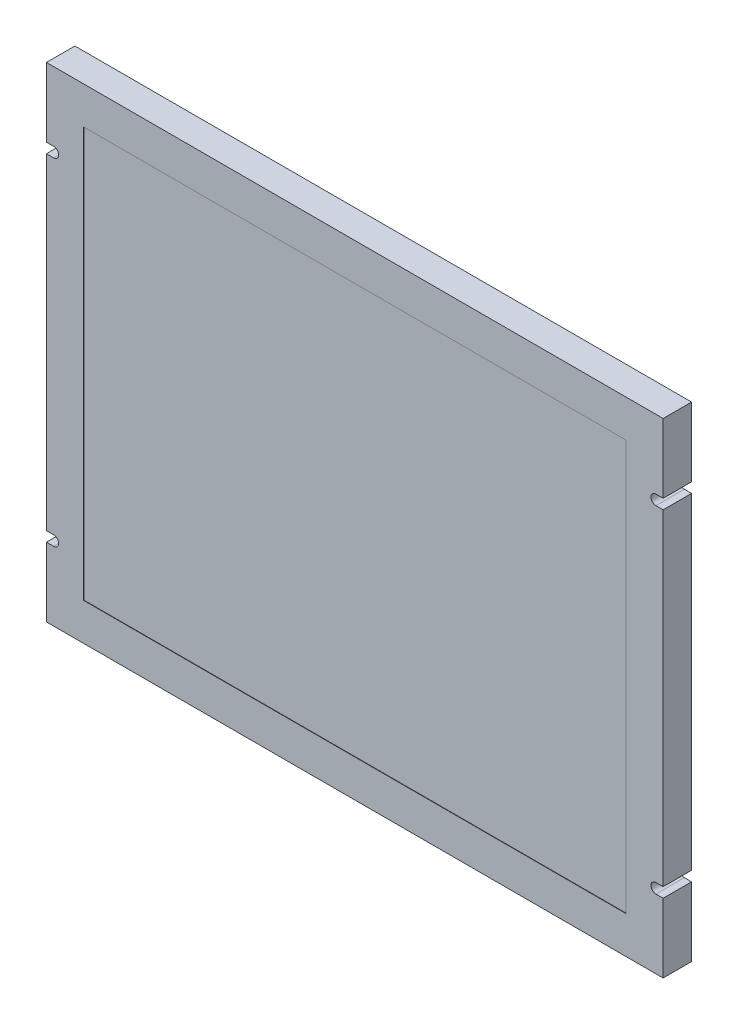
SolidWorks part; units mm, degrees
ref_plane "Front" through (0, 0, 0) normal (0, 0, 1) x (1, 0, 0)
ref_plane "Top" through (0, 0, 0) normal (0, 1, 0) x (1, 0, 0)
ref_plane "Right" through (0, 0, 0) normal (1, 0, 0) x (0, 0, -1)
sketch "Sketch1" plane through (0, 0, 0) normal (0, 0, 1) x (1, 0, 0)
  line L1 (0, 0) -> (154, 0)
  line L2 (0, 0) -> (0, -121)
  line L3 (0, -121) -> (154, -121)
  line L4 (154, 0) -> (154, -121)
  dimension "D1" = 154
  dimension "D2" = 121
extrude "Extrude1" add sketch "Sketch1" along normal blind 7.1
sketch "Sketch2" plane through (0, 0, 7.1) normal (0, 0, 1) x (1, 0, 0)
  line L0 (154, -121) -> (154, 0) construction
  line L1 (9.25, -9.3) -> (144.75, -9.3)
  line L2 (9.25, -9.3) -> (9.25, -111.7)
  line L3 (9.25, -111.7) -> (144.75, -111.7)
  line L4 (144.75, -9.3) -> (144.75, -111.7)
  line L5 (154, 0) -> (0, 0) construction
  dimension "D1" = 135.5
  dimension "D2" = 102.4
  dimension "D3" = 9.25
  dimension "D4" = 9.3
extrude "Bezel Opening" cut sketch "Sketch2" against normal blind 0.1
sketch "Sketch3" plane through (0, 0, 7.1) normal (0, 0, 1) x (1, 0, 0)
  line L2 (154, -17.25) -> (152.2, -17.25)
  line L3 (154, -121) -> (154, 0) construction
  line L4 (154, -19.75) -> (152.2, -19.75)
  line L5 (154, 0) -> (0, 0) construction
  arc A0 (152.2, -19.75) -> (152.2, -17.25) centre (152.2, -18.5) cw
  arc A1 (154, -17.25) -> (154, -19.75) centre (154, -18.5) cw
  dimension "D1" = 2.5
  dimension "D3" = 18.5
  dimension "D2" = 1.8
extrude "Cut-Extrude3" cut sketch "Sketch3" against normal blind 10
pattern_linear "LPattern1" count 2 spacing 84 along (0, -1, 0) count 2 spacing 152.2 along (-1, 0, 0) of "Cut-Extrude3"
sketch "Sketch4" plane through (0, 0, 7.1) normal (0, 0, 1) x (1, 0, 0)
  line L0 (77, 0) -> (77, -121) construction
  line L1 (154, 0) -> (0, 0) construction
  line L2 (0, -121) -> (154, -121) construction
  line L3 (0, -60.5) -> (154, -60.5) construction
  line L4 (0, 0) -> (0, -17.25) construction
  line L5 (154, -101.25) -> (154, -19.75) construction
sketch "Sketch5" plane through (0, 0, 0) normal (0, 1, 0) x (-1, 0, 0)
  line L0 (-77, 0) -> (-77, 7.1) construction
  line L1 (0, 0) -> (-154, 0) construction
  line L2 (0, 7.1) -> (-154, 7.1) construction
